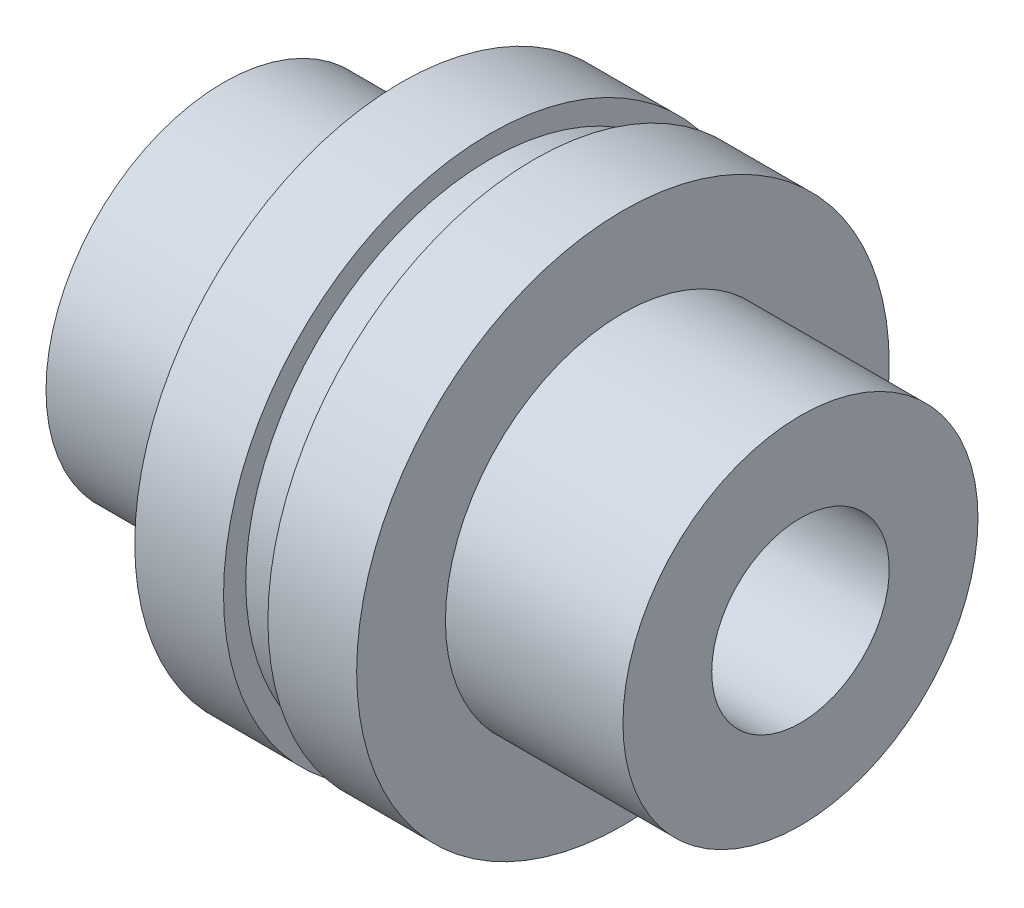
SolidWorks part; units mm, degrees
material "PW50:6:Ar:0:-1:C1:1:2:3:Re:11:"
ref_plane "front" through (0, 0, 0) normal (0, 0, 1) x (1, 0, 0)
ref_plane "top" through (0, 0, 0) normal (0, 1, 0) x (1, 0, 0)
ref_plane "side" through (0, 0, 0) normal (1, 0, 0) x (0, 0, -1)
sketch "Sketch1" plane through (0, 0, 0) normal (0, 0, 1) x (1, 0, 0)
  line L0 (0, 0) -> (65.5339, 0) construction
  line L1 (0, 12.7) -> (0, 25.4)
  line L2 (0, 25.4) -> (25.4, 25.4)
  line L3 (25.4, 25.4) -> (25.4, 38.1)
  line L4 (25.4, 38.1) -> (38.1, 38.1)
  line L5 (38.1, 38.1) -> (38.1, 34.925)
  line L6 (38.1, 34.925) -> (44.45, 34.925)
  line L7 (41.275, 34.925) -> (41.275, 0) construction
  line L8 (0, 12.7) -> (82.55, 12.7)
  line L9 (0, -50) -> (0, 50) construction
  line L10 (44.45, 38.1) -> (44.45, 34.925)
  line L11 (57.15, 38.1) -> (44.45, 38.1)
  line L12 (57.15, 25.4) -> (57.15, 38.1)
  line L13 (82.55, 25.4) -> (57.15, 25.4)
  line L14 (82.55, 12.7) -> (82.55, 25.4)
  point P15 (41.275, 12.7)
  point P16 (41.275, 34.925)
  dimension "D1" = 12.7
  dimension "D2" = 25.4
  dimension "D3" = 38.1
  dimension "D4" = 3.175
  dimension "D5" = 25.4
  dimension "D6" = 38.1
  dimension "D7" = 3.175
revolve "Base-Revolve" add sketch "Sketch1" angle 360 about L0
